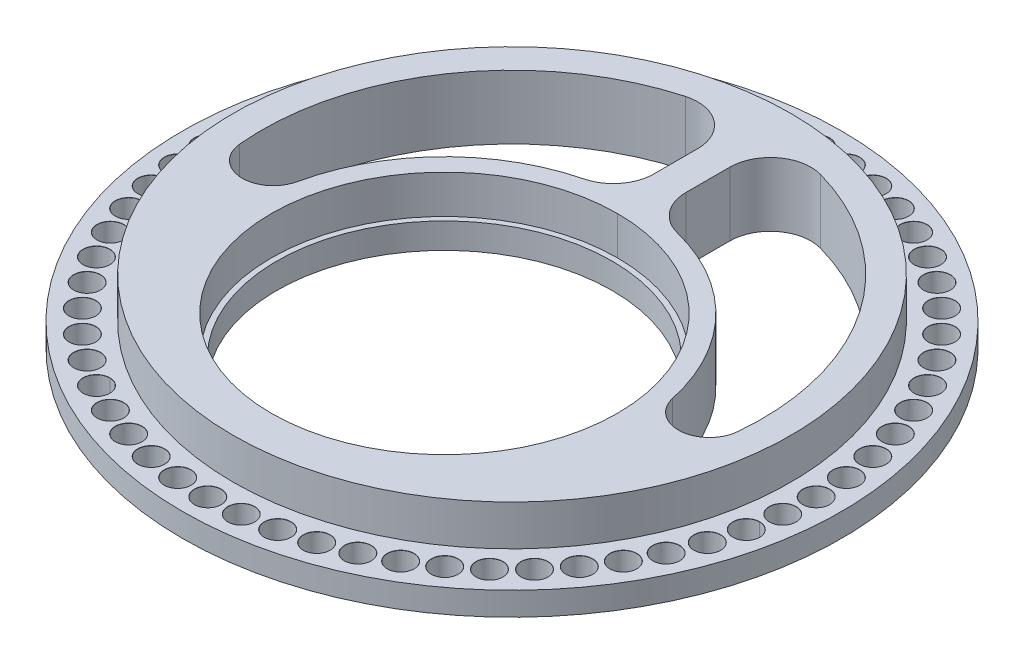
SolidWorks part; units mm, degrees
material "6061-T6 (SS)"
ref_plane "X-Y Datum" through (0, 0, 0) normal (0, 0, 1) x (1, 0, 0)
ref_plane "X-Z Datum" through (0, 0, 0) normal (0, 1, 0) x (1, 0, 0)
ref_plane "Y-Z Datum" through (0, 0, 0) normal (1, 0, 0) x (0, 0, -1)
sketch "Sketch1" plane through (0, 0, 0) normal (0, 1, 0) x (1, 0, 0)
  line L0 (0, 0) -> (0, -12.7) construction
  line L1 (0, -43.0151) -> (0, 43.0151) construction
  line L2 (0, 52.3875) -> (0, 61.9125) construction
  circle A0 centre (0, -12.7) radius 30.988
  circle A1 centre (0, 0) radius 52.3875 construction
  circle A2 centre (0, 0) radius 61.9125
  circle A3 centre (0, 0) radius 57.15 construction
  point P12 (0, 57.15)
  dimension "D2" = 61.976
  dimension "D3" = 104.775
  dimension "D4" = 123.825
  dimension "D5" = 114.3
  dimension "D1" = 12.7
extrude "Slotted-Body Extrude" add sketch "Sketch1" along normal blind 4.191 and the other way blind 0.2032
sketch "Sketch5" plane through (0, 4.191, 0) normal (0, 1, 0) x (1, 0, 0)
  circle A0 centre (0, 0) radius 52.3875 construction
  circle A1 centre (0, 0) radius 52.3875
extrude "Boss-Extrude3" add sketch "Sketch5" along normal blind 7.62
sketch "Sketch6" plane through (0, -0.2032, 0) normal (0, -1, 0) x (1, 0, 0)
  line L0 (0, -79.2756) -> (0, 0) construction
  line L2 (3.014, -37.9067) -> (3.014, -29.6741)
  line L4 (-3.014, -37.9067) -> (-3.014, -29.6741)
  circle A0 centre (0, 12.7) radius 30.988 construction
  circle A1 centre (0, 12.7) radius 30.988 construction
  circle A2 centre (0, 12.7) radius 32.512
  arc A9 (-35.2562, 5.0907) -> (-8.7792, -22.2832) centre (0, 12.7) ccw
  arc A10 (-46.783, 4.406) -> (-12.6921, -45.2435) centre (0, 0) ccw
  arc A11 (-46.783, 4.406) -> (-35.2562, 5.0907) centre (-40.9667, 3.8583) cw
  arc A19 (-3.014, -29.6741) -> (-8.7792, -22.2832) centre (-10.634, -29.6741) ccw
  arc A20 (-3.014, -37.9067) -> (-12.6921, -45.2435) centre (-10.634, -37.9067) cw
  circle A21 centre (0, 0) radius 61.9125 construction
  arc A27 (46.783, 4.406) -> (35.2562, 5.0907) centre (40.9667, 3.8583) ccw
  arc A28 (46.783, 4.406) -> (12.6921, -45.2435) centre (0, 0) cw
  arc A29 (3.014, -37.9067) -> (12.6921, -45.2435) centre (10.634, -37.9067) ccw
  arc A30 (3.014, -29.6741) -> (8.7792, -22.2832) centre (10.634, -29.6741) cw
  arc A31 (35.2562, 5.0907) -> (8.7792, -22.2832) centre (0, 12.7) cw
  point P30 (0, 0)
  point P31 (-3.014, -23.2419)
  point P32 (0, 0)
  point P36 (-3.014, -46.8932)
  dimension "D1" = 65.024
  dimension "D2" = 7.62
  dimension "D3" = 5.842
  dimension "D4" = 46.99
  dimension "D5" = 7.62
  dimension "D6" = 36.068
  dimension "D8" = 8.2326
extrude "Cut-Extrude5" cut sketch "Sketch6" against normal through all
sketch "Sketch8" plane through (0, -0.2032, 0) normal (0, -1, 0) x (1, 0, 0)
  circle A0 centre (0, 12.7) radius 32.512 construction
  circle A1 centre (0, 12.7) radius 32.512
  circle A2 centre (0, 12.7) radius 31.496
  dimension "D1" = 62.992
extrude "Boss-Extrude4" add sketch "Sketch8" against normal blind 4.795 separate body
hole_wizard "Ø5.0mm Dowel Hole2" positions "Sketch9" profile "Sketch10" hole size "Ø5.0" standard "ANSI Metric" end condition through all
sketch "Sketch9" plane through (0, 4.191, 0) normal (0, 1, 0) x (1, 0, 0)
  point P0 (0, 57.15)
sketch "Sketch10" plane through (0, 4.191, -57.15) normal (1, 0, 0) x (0, 0, 1)
  line L0 (0, 0) -> (0, 4.3942)
  line L1 (0, 4.3942) -> (2.5, 4.3942)
  line L2 (2.5, 4.3942) -> (2.5, 0.025)
  line L3 (2.5, 0.025) -> (2.525, 0)
  line L5 (2.525, 0) -> (0, 0)
  line L6 (-2.5, 0.025) -> (-2.525, 0) construction
  line L11 (0, -6.35) -> (0, 107.95) construction
  dimension "Thru Hole Dia." = 5
  dimension "Thru Hole Depth" = 4.3942
  dimension "Near C'Sink Dia." = 5.05
  dimension "Near C'Sink Angle" = 90
pattern_circular "CirPattern1" count 60 over 360 about axis through (0, 0, 0) along (0, 1, 0) of "Ø5.0mm Dowel Hole2"
ref_point "Point1"
ref_plane "Plane1" through (0, 0, 0) normal (1, 0, 0) x (0, 0, -1)
split line "Split Line1"
ref_point "Point2"
ref_point "Point3"
ref_point "Point4"
ref_point "Point5"
split line "Split Line2"
split line "Split Line3"
ref_plane "Plane2" through (-42.4707, 0, 0) normal (-1, 0, 0) x (0, 0, 1)
ref_plane "Plane3" through (55.9011, 0, 0) normal (-1, 0, 0) x (0, 0, 1)
split line "Split Line4"
split line "Split Line5"
sketch "Sketch11" plane through (0, -0.2032, 0) normal (0, -1, 0) x (1, 0, 0)
  line L1 (-61.9125, -61.9125) -> (61.9125, -61.9125)
  line L2 (-61.9125, -61.9125) -> (-61.9125, 61.9125)
  line L3 (-61.9125, 61.9125) -> (61.9125, 61.9125)
  line L4 (61.9125, -61.9125) -> (61.9125, 61.9125)
  line L5 (-61.9125, -61.9125) -> (61.9125, 61.9125) construction
  line L6 (-61.9125, 61.9125) -> (61.9125, -61.9125) construction
  circle A0 centre (0, 0) radius 61.9125 construction
  point P0 (0, 0)
sketch "Sketch13" plane through (0, 11.811, 0) normal (0, 1, 0) x (1, 0, 0)
  line L0 (3.014, 29.6741) -> (3.014, 37.9067) construction
  line L1 (-3.014, 37.9067) -> (-3.014, 29.6741) construction
  line L2 (3.014, 29.6741) -> (3.014, 37.9067) construction
  line L3 (-3.014, 37.9067) -> (-3.014, 29.6741) construction
  line L4 (-6.062, 37.9067) -> (-6.062, 29.6741)
  line L5 (6.062, 29.6741) -> (6.062, 37.9067)
  circle A0 centre (0, -12.7) radius 31.496 construction
  circle A1 centre (0, -12.7) radius 31.496 construction
  circle A2 centre (0, -12.7) radius 28.448
  arc A3 (35.2562, -5.0907) -> (46.783, -4.406) centre (40.9667, -3.8583) ccw construction
  arc A4 (35.2562, -5.0907) -> (8.7792, 22.2832) centre (0, -12.7) ccw construction
  arc A5 (3.014, 29.6741) -> (8.7792, 22.2832) centre (10.634, 29.6741) ccw construction
  arc A6 (46.783, -4.406) -> (12.6921, 45.2435) centre (0, 0) ccw construction
  arc A7 (12.6921, 45.2435) -> (3.014, 37.9067) centre (10.634, 37.9067) ccw construction
  arc A8 (-46.783, -4.406) -> (-35.2562, -5.0907) centre (-40.9667, -3.8583) ccw construction
  arc A9 (-8.7792, 22.2832) -> (-35.2562, -5.0907) centre (0, -12.7) ccw construction
  arc A10 (-8.7792, 22.2832) -> (-3.014, 29.6741) centre (-10.634, 29.6741) ccw construction
  arc A11 (-3.014, 37.9067) -> (-12.6921, 45.2435) centre (-10.634, 37.9067) ccw construction
  arc A12 (-12.6921, 45.2435) -> (-46.783, -4.406) centre (0, 0) ccw construction
  arc A13 (35.2562, -5.0907) -> (46.783, -4.406) centre (40.9667, -3.8583) ccw construction
  arc A14 (35.2562, -5.0907) -> (8.7792, 22.2832) centre (0, -12.7) ccw construction
  arc A15 (3.014, 29.6741) -> (8.7792, 22.2832) centre (10.634, 29.6741) ccw construction
  arc A16 (46.783, -4.406) -> (12.6921, 45.2435) centre (0, 0) ccw construction
  arc A17 (12.6921, 45.2435) -> (3.014, 37.9067) centre (10.634, 37.9067) ccw construction
  arc A18 (-46.783, -4.406) -> (-35.2562, -5.0907) centre (-40.9667, -3.8583) ccw construction
  arc A19 (-8.7792, 22.2832) -> (-35.2562, -5.0907) centre (0, -12.7) ccw construction
  arc A20 (-8.7792, 22.2832) -> (-3.014, 29.6741) centre (-10.634, 29.6741) ccw construction
  arc A21 (-3.014, 37.9067) -> (-12.6921, 45.2435) centre (-10.634, 37.9067) ccw construction
  arc A22 (-12.6921, 45.2435) -> (-46.783, -4.406) centre (0, 0) ccw construction
  arc A23 (-11.8689, 42.3087) -> (-43.7484, -4.1202) centre (0, 0) ccw
  arc A24 (-43.7484, -4.1202) -> (-38.2356, -4.4477) centre (-40.9667, -3.8583) ccw
  arc A25 (-9.5211, 25.2396) -> (-38.2356, -4.4477) centre (0, -12.7) ccw
  arc A26 (-9.5211, 25.2396) -> (-6.062, 29.6741) centre (-10.634, 29.6741) ccw
  arc A27 (-6.062, 37.9067) -> (-11.8689, 42.3087) centre (-10.634, 37.9067) ccw
  arc A28 (11.8689, 42.3087) -> (6.062, 37.9067) centre (10.634, 37.9067) ccw
  arc A29 (6.062, 29.6741) -> (9.5211, 25.2396) centre (10.634, 29.6741) ccw
  arc A30 (38.2356, -4.4477) -> (9.5211, 25.2396) centre (0, -12.7) ccw
  arc A31 (38.2356, -4.4477) -> (43.7484, -4.1202) centre (40.9667, -3.8583) ccw
  arc A32 (43.7484, -4.1202) -> (11.8689, 42.3087) centre (0, 0) ccw
  dimension "D1" = 3.048
  dimension "D2" = 3.048
sketch "Sketch14" plane through (0, 4.191, 0) normal (0, 1, 0) x (1, 0, 0)
  line L0 (-61.9125, 61.9125) -> (-61.9125, -61.9125) construction
  line L1 (-61.9125, 61.9125) -> (61.9125, 61.9125) construction
  line L2 (-61.9125, 61.9125) -> (-61.9125, -61.9125) construction
  line L3 (-61.9125, 61.9125) -> (61.9125, 61.9125) construction
  line L7 (-61.9125, -61.9125) -> (61.9125, 61.9125) construction
  line L8 (-61.9125, -61.9125) -> (61.9125, 61.9125)
  line L9 (0, -0.6085) -> (0, 49999.3915) construction
  circle A0 centre (0, 0) radius 61.9125 construction
  circle A2 centre (0, 0) radius 61.9125 construction
  arc A3 (-62.4462, 2.4493) -> (62.4462, 2.4493) centre (0, -0.6085) cw
  arc A4 (-62.4462, 2.4493) -> (-77.6194, 1.8864) centre (-70.0571, 2.822) cw
  arc A5 (0, 61.9125) -> (-3.7531, 76.0115) centre (-4.0041, 68.3957) ccw
  arc A6 (-77.6194, 1.8864) -> (-3.7531, 76.0115) centre (-26.007, 24.3209) cw
  arc A7 (2.4493, -62.4462) -> (1.8864, -77.6194) centre (2.822, -70.0571) ccw
  arc A8 (2.4493, -62.4462) -> (61.9125, 0) centre (-0.6085, 0) ccw
  arc A9 (61.9125, 0) -> (76.0115, -3.7531) centre (68.3957, -4.0041) cw
  arc A10 (1.8864, -77.6194) -> (76.0115, -3.7531) centre (24.3209, -26.007) ccw
  arc A11 (62.4462, 2.4493) -> (77.6194, 1.8864) centre (70.0571, 2.822) ccw
  arc A12 (0, 61.9125) -> (3.7531, 76.0115) centre (4.0041, 68.3957) cw
  arc A13 (77.6194, 1.8864) -> (3.7531, 76.0115) centre (26.007, 24.3209) ccw
  arc A14 (-2.4493, -62.4462) -> (-61.9125, 0) centre (0.6085, 0) cw
  arc A15 (-61.9125, 0) -> (-76.0115, -3.7531) centre (-68.3957, -4.0041) ccw
  arc A16 (-1.8864, -77.6194) -> (-76.0115, -3.7531) centre (-24.3209, -26.007) cw
  arc A17 (-2.4493, -62.4462) -> (-1.8864, -77.6194) centre (-2.822, -70.0571) cw
  point P13 (-61.9125, 0)
  dimension "D1" = 7.62
  dimension "D2" = 7.62
sketch "Sketch17" plane through (0, 4.191, 0) normal (0, 1, 0) x (1, 0, 0)
  line L0 (-71.12, 66.6242) -> (71.12, 66.6242) construction
  line L1 (-71.12, -66.6242) -> (71.12, -66.6242) construction
  line L2 (-71.12, -66.6242) -> (-71.12, 66.6242) construction
  line L3 (-71.12, 66.6242) -> (71.12, 66.6242) construction
  line L4 (71.12, -66.6242) -> (71.12, 66.6242) construction
  line L5 (-71.12, -66.6242) -> (71.12, 66.6242) construction
  line L6 (-71.12, 66.6242) -> (-45.1836, 42.3273) construction
  line L7 (-71.12, 88.7603) -> (71.12, 88.7603)
  line L11 (-71.12, 59.8198) -> (-15.9607, 59.8198)
  line L12 (-71.12, 88.7603) -> (71.12, 88.7603)
  line L13 (-71.12, 88.7603) -> (-71.12, -66.6242)
  line L14 (-71.12, -66.6242) -> (71.12, -66.6242)
  line L15 (71.12, 88.7603) -> (71.12, -66.6242)
  line L16 (15.9607, 59.8198) -> (71.12, 59.8198)
  line L17 (0, 0) -> (71.12, -66.6242) construction
  arc A1 (15.9607, 59.8198) -> (-15.9607, 59.8198) centre (0, 0) ccw
  point P0 (0, 0)
  dimension "D1" = 142.24
  dimension "D2" = 133.2484
  dimension "D3" = 22.1361
